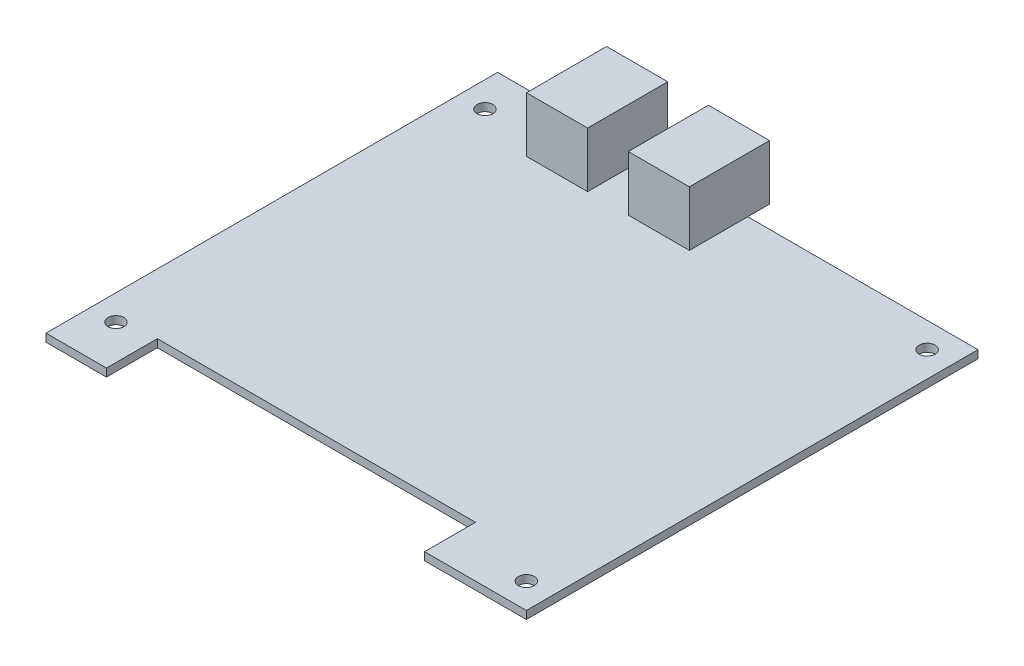
SolidWorks part; units mm, degrees
material "E-Glass Fiber"
ref_plane "Front Plane" through (0, 0, 0) normal (0, 0, 1) x (1, 0, 0)
ref_plane "Top Plane" through (0, 0, 0) normal (0, 1, 0) x (1, 0, 0)
ref_plane "Right Plane" through (0, 0, 0) normal (1, 0, 0) x (0, 0, -1)
sketch "Sketch1" plane through (0, 0, 0) normal (0, 1, 0) x (1, 0, 0)
  line L0 (-35.875, -45.085) -> (-47.945, -45.085)
  line L1 (47.945, -45.085) -> (27.625, -45.085)
  line L2 (47.945, -45.085) -> (47.945, 45.085)
  line L3 (47.945, 45.085) -> (-47.945, 45.085)
  line L4 (-47.945, -45.085) -> (-47.945, 45.085)
  line L5 (47.945, -45.085) -> (-47.945, 45.085) construction
  line L6 (47.945, 45.085) -> (-47.945, -45.085) construction
  line L8 (-35.875, -45.085) -> (-35.875, -34.925)
  line L9 (-35.875, -34.925) -> (27.625, -34.925)
  line L10 (27.625, -45.085) -> (27.625, -34.925)
  point P0 (0, 0)
  dimension "D1" = 90.17
  dimension "D2" = 95.89
  dimension "D3" = 20.32
  dimension "D4" = 10.16
  dimension "D5" = 83.82
extrude "Boss-Extrude1" add sketch "Sketch1" along normal blind 1.57
sketch "Sketch2" plane through (0, 1.57, 0) normal (0, 1, 0) x (1, 0, 0)
  line L0 (27.625, -45.085) -> (47.945, -45.085) construction
  line L1 (47.945, -45.085) -> (47.945, 45.085) construction
  circle A0 centre (42.865, -40.005) radius 1.59
  circle A1 centre (-42.865, -36.195) radius 1.59
  circle A2 centre (-42.865, 37.465) radius 1.59
  circle A3 centre (42.865, 40.005) radius 1.59
  dimension "D3" = 3.18
  dimension "D6" = 3.18
  dimension "D9" = 3.18
  dimension "D12" = 3.18
  dimension "D1" = 5.08
  dimension "D2" = 5.08
  dimension "D4" = 8.89
  dimension "D5" = 90.81
  dimension "D7" = 5.08
  dimension "D8" = 85.09
  dimension "D10" = 90.81
  dimension "D11" = 82.55
extrude "Cut-Extrude1" cut sketch "Sketch2" against normal through all
sketch "Sketch3" plane through (0, 1.57, 0) normal (0, 1, 0) x (1, 0, 0)
  line L0 (47.945, 45.085) -> (-47.945, 45.085) construction
  line L1 (-30.545, 49.435) -> (-18.345, 49.435)
  line L2 (-30.545, 49.435) -> (-30.545, 33.435)
  line L3 (-30.545, 33.435) -> (-18.345, 33.435)
  line L4 (-18.345, 49.435) -> (-18.345, 33.435)
  line L5 (-10.225, 49.435) -> (1.975, 49.435)
  line L6 (-10.225, 49.435) -> (-10.225, 33.435)
  line L7 (-10.225, 33.435) -> (1.975, 33.435)
  line L8 (1.975, 49.435) -> (1.975, 33.435)
  line L9 (47.945, -45.085) -> (47.945, 45.085) construction
  dimension "D1" = 16
  dimension "D2" = 16
  dimension "D3" = 12.2
  dimension "D4" = 12.2
  dimension "D5" = 4.35
  dimension "D6" = 4.35
  dimension "D7" = 45.97
  dimension "D8" = 20.32
extrude "Boss-Extrude2" add sketch "Sketch3" along normal blind 11 separate body
